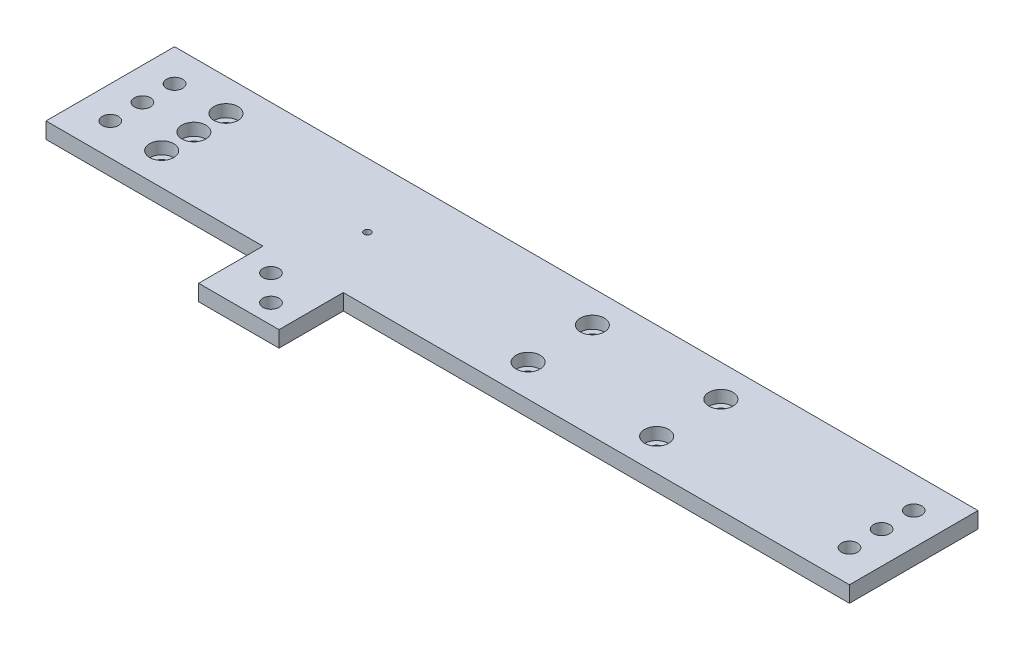
SolidWorks part; units mm, degrees
material "6061-T6 (SS)"
ref_plane "Front" through (0, 0, 0) normal (0, 0, 1) x (1, 0, 0)
ref_plane "Top" through (0, 0, 0) normal (0, 1, 0) x (1, 0, 0)
ref_plane "Right" through (0, 0, 0) normal (1, 0, 0) x (0, 0, -1)
sketch "Sketch1" plane through (0, 0, 0) normal (0, 1, 0) x (1, 0, 0)
  line L1 (-158.75, -25.4) -> (158.75, -25.4)
  line L2 (-158.75, -25.4) -> (-158.75, 25.4)
  line L3 (-158.75, 25.4) -> (158.75, 25.4)
  line L4 (158.75, -25.4) -> (158.75, 25.4)
  line L5 (-158.75, -25.4) -> (158.75, 25.4) construction
  line L6 (-158.75, 25.4) -> (158.75, -25.4) construction
  point P0 (0, 0)
  dimension "D1" = 50.8
  dimension "D2" = 317.5
extrude "Boss-Extrude1" add sketch "Sketch1" along normal blind 6.35
hole_wizard "CBORE for #10 Socket Head Cap Screw1" positions "Sketch2" profile "Sketch4" counterbore size "#10" standard "ANSI Inch" end condition through all
sketch "Sketch2" plane through (0, 6.35, 0) normal (0, 1, 0) x (1, 0, 0)
  line L2 (158.75, 25.4) -> (-158.75, 25.4) construction
  line L6 (-158.75, -25.4) -> (158.75, -25.4) construction
  line L8 (-158.75, 25.4) -> (-158.75, -25.4) construction
  line L12 (158.75, -25.4) -> (158.75, 25.4) construction
  line L15 (19.05, 12.7) -> (19.05, 25.4) construction
  line L17 (19.05, -12.7) -> (19.05, -25.4) construction
  line L18 (-125.73, -25.4) -> (-125.73, -12.7) construction
  line L20 (-125.73, 0) -> (-125.73, 12.7) construction
  line L21 (-125.73, 12.7) -> (-125.73, 25.4) construction
  line L22 (-125.73, 0) -> (-125.73, -12.7) construction
  point P64 (19.05, 12.7)
  point P66 (69.85, 12.7)
  point P68 (19.05, -12.7)
  point P70 (69.85, -12.7)
  point P92 (-125.73, 12.7)
  point P94 (-125.73, 0)
  point P102 (-125.73, -12.7)
  dimension "D2" = 50.8
  dimension "D3" = 25.4
  dimension "D4" = 88.9
  dimension "D5" = 33.02
sketch "Sketch4" plane through (-125.73, 6.35, 12.7) normal (1, 0, 0) x (0, 0, 1)
  line L0 (0, 0) -> (0, 6.35)
  line L1 (0, 6.35) -> (2.5527, 6.35)
  line L3 (2.5527, 6.35) -> (2.5527, 4.826)
  line L4 (2.5527, 4.826) -> (4.7625, 4.826)
  line L5 (4.7625, 4.826) -> (4.7625, 0)
  line L7 (4.7625, 0) -> (0, 0)
  line L11 (0, -6.35) -> (0, 107.95) construction
  dimension "Thru Hole Dia." = 5.1054
  dimension "Thru Hole Depth" = 6.35
  dimension "C'Bore Dia." = 9.525
  dimension "C'Bore Depth" = 4.826
sketch "Sketch7" plane through (0, 0, 0) normal (0, -1, 0) x (1, 0, 0)
  line L0 (-146.05, 25.4) -> (-146.05, 12.7) construction
  line L1 (-158.75, 25.4) -> (158.75, 25.4) construction
  line L2 (-146.05, 12.7) -> (-146.05, 0) construction
  line L3 (-146.05, 0) -> (-146.05, -12.7) construction
  line L4 (-146.05, -12.7) -> (-146.05, -25.4) construction
  line L5 (158.75, -25.4) -> (-158.75, -25.4) construction
  line L7 (-158.75, -25.4) -> (-158.75, 25.4) construction
  line L8 (146.05, 25.4) -> (146.05, 12.7) construction
  line L9 (146.05, 12.7) -> (146.05, 0) construction
  line L10 (146.05, 0) -> (146.05, -12.7) construction
  line L11 (146.05, -12.7) -> (146.05, -25.4) construction
  line L13 (158.75, 25.4) -> (158.75, -25.4) construction
  point P0 (-146.05, 12.7)
  point P2 (-146.05, 0)
  point P4 (-146.05, -12.7)
  point P6 (146.05, 12.7)
  point P8 (146.05, 0)
  point P10 (146.05, -12.7)
  dimension "D1" = 12.7
  dimension "D2" = 12.7
hole_wizard "1/4 (0.25) Diameter Hole1" positions "Sketch7" profile "Sketch6" hole size "1/4" standard "ANSI Inch" end condition through all
sketch "Sketch6" plane through (-146.05, 0, 12.7) normal (1, 0, 0) x (0, 0, -1)
  line L0 (0, 0) -> (0, 6.35)
  line L1 (0, 6.35) -> (3.175, 6.35)
  line L2 (3.175, 6.35) -> (3.175, 0)
  line L5 (3.175, 0) -> (0, 0)
  line L11 (0, -6.35) -> (0, 107.95) construction
  dimension "Thru Hole Dia." = 6.35
  dimension "Thru Hole Depth" = 6.35
sketch "Sketch10" plane through (0, 0, 0) normal (0, -1, 0) x (-1, 0, 0)
  line L0 (158.75, 25.4) -> (158.75, -25.4) construction
  point P0 (57.15, 0)
  dimension "D1" = 101.6
hole_wizard "#6-32 Tapped Hole1" positions "Sketch10" profile "Sketch9" tap size "#6-32" standard "ANSI Inch" end condition through all
sketch "Sketch9" plane through (-57.15, 0, 0) normal (1, 0, 0) x (0, 0, -1)
  line L0 (0, 0) -> (0, 6.35)
  line L1 (0, 6.35) -> (1.3525, 6.35)
  line L2 (1.3525, 6.35) -> (1.3525, 0)
  line L5 (1.3525, 0) -> (0, 0)
  line L11 (0, -6.35) -> (0, 107.95) construction
  dimension "Thru Tap Drill Dia." = 2.7051
  dimension "Thru Tap Drill Depth" = 6.35
cosmetic thread "Hole Thread1" parameters "D2"=3.5052
sketch "Sketch11" plane through (0, 0, 0) normal (0, -1, 0) x (1, 0, 0)
  line L0 (158.75, -25.4) -> (-158.75, -25.4) construction
  line L1 (-70.0118, -25.4) -> (-48.1024, -25.4)
  line L2 (-70.0118, -25.4) -> (-70.0118, -45.81)
  line L3 (-70.0118, -45.81) -> (-48.1024, -45.81)
  line L4 (-48.1024, -25.4) -> (-48.1024, -45.81)
extrude "Boss-Extrude2" [suppressed] add sketch "Sketch11" against normal up to surface (6.35 mm away)
sketch "Sketch12" plane through (0, 6.35, 0) normal (0, 1, 0) x (1, 0, 0)
  line L0 (-158.75, -25.4) -> (158.75, -25.4) construction
  line L1 (-73.025, -25.4) -> (-41.275, -25.4)
  line L2 (-73.025, -25.4) -> (-73.025, -50.8)
  line L3 (-73.025, -50.8) -> (-41.275, -50.8)
  line L4 (-41.275, -25.4) -> (-41.275, -50.8)
  line L5 (-158.75, 25.4) -> (-158.75, -25.4) construction
  dimension "D1" = 85.725
  dimension "D2" = 31.75
  dimension "D3" = 25.4
extrude "Boss-Extrude3" add sketch "Sketch12" against normal up to surface (6.35 mm away) up to face at (-57.15, 0, -1.3526)
sketch "Sketch15" plane through (0, 0, 0) normal (0, -1, 0) x (-1, 0, 0)
  point P0 (52.07, -43.18)
  point P3 (62.23, -33.02)
hole_wizard "1/4 (0.25) Diameter Hole2" positions "Sketch15" profile "Sketch14" hole size "1/4" standard "ANSI Inch" end condition through all
sketch "Sketch14" plane through (-52.07, 0, 43.18) normal (1, 0, 0) x (0, 0, -1)
  line L0 (0, 0) -> (0, 6.35)
  line L1 (0, 6.35) -> (3.175, 6.35)
  line L2 (3.175, 6.35) -> (3.175, 0)
  line L5 (3.175, 0) -> (0, 0)
  line L11 (0, -6.35) -> (0, 107.95) construction
  dimension "Thru Hole Dia." = 6.35
  dimension "Thru Hole Depth" = 6.35
